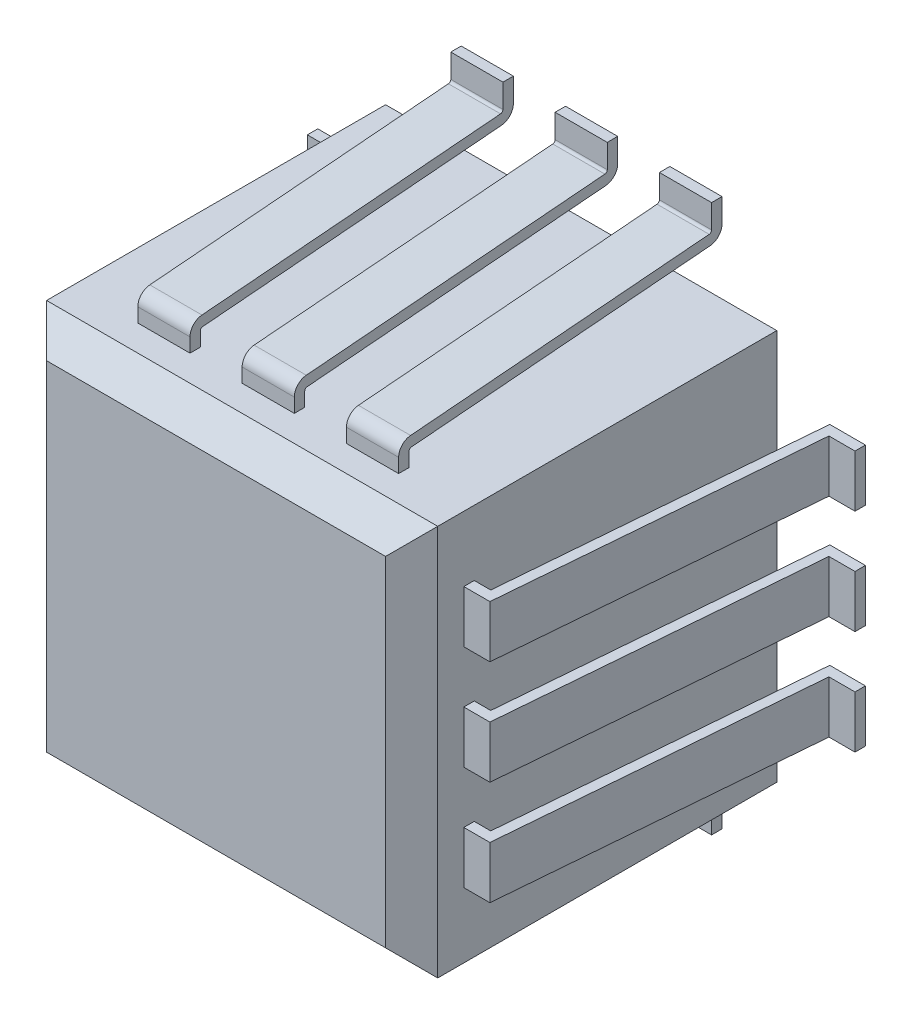
SolidWorks part; units mm, degrees
ref_plane "Front" through (0, 0, 0) normal (0, 0, 1) x (1, 0, 0)
ref_plane "Top" through (0, 0, 0) normal (0, 1, 0) x (1, 0, 0)
ref_plane "Right" through (0, 0, 0) normal (1, 0, 0) x (0, 0, -1)
sketch "COMPONENT_OUTLINE" plane through (0, 0, 0) normal (0, 0, 1) x (1, 0, 0)
  line L0 (-0.75, 0.75) -> (-0.75, -0.75)
  line L1 (-0.75, -0.75) -> (0.75, -0.75)
  line L2 (0.75, -0.75) -> (0.75, 0.75)
  line L3 (0.75, 0.75) -> (-0.75, 0.75)
  line L4 (-0.75, 0.75) -> (0.75, -0.75) construction
  line L5 (-0.75, -0.75) -> (0.75, 0.75) construction
  dimension "D1" = 1.5
  dimension "D2" = 1.5
extrude "Extrude1" add sketch "COMPONENT_OUTLINE" along normal blind 1.4
sketch "Sketch1" plane through (0, 0, 0) normal (1, 0, 0) x (0, 0, -1)
  line L0 (-1.2, 0.75) -> (-1.2, 0.85)
  line L1 (-1.4, 0.75) -> (0, 0.75) construction
  line L2 (-1.2, 0.85) -> (0, 0.95)
  line L3 (0, 0.95) -> (0, 1.05)
  dimension "D1" = 0.1
  dimension "D2" = 0.2
  dimension "D3" = 0.2
  dimension "D4" = 0.1
extrude "Extrude-Thin1" add sketch "Sketch1" along normal mid plane 0.2 thin
pattern_linear "LPattern1" count 2 spacing 0.4 along (-1, 0, 0) count 2 spacing 0.4 along (1, 0, 0) of "Extrude-Thin1"
mirror "Mirror1" about plane through (0, 0, 0) normal (0, 1, 0) of "Extrude-Thin1", "LPattern1"
sketch "Sketch2" plane through (0, 0, 0) normal (0, 1, 0) x (1, 0, 0)
  line L0 (0.75, -1.2) -> (0.85, -1.2)
  line L1 (0.75, -1.4) -> (0.75, 0) construction
  line L2 (0.85, -1.2) -> (0.95, 0)
  line L3 (0.95, 0) -> (1.05, 0)
  line L4 (0.75, -1.4) -> (-0.75, -1.4) construction
  dimension "D1" = 0.1
  dimension "D2" = 0.2
  dimension "D3" = 0.2
  dimension "D4" = 0.1
extrude "Extrude-Thin2" add sketch "Sketch2" along normal mid plane 0.2 thin thin type one direction reverse wall 0.04
pattern_linear "LPattern2" count 2 spacing 0.4 along (0, 1, 0) count 2 spacing 0.4 along (0, -1, 0) of "Extrude-Thin2"
mirror "Mirror2" about plane through (0, 0, 0) normal (1, 0, 0) of "LPattern2", "Extrude-Thin2"
chamfer "Chamfer1" distance 0.1 angle 45 4 edges at (0.75, 0, 1.4) (0, -0.75, 1.4) (-0.75, 0, 1.4) (0, 0.75, 1.4)
